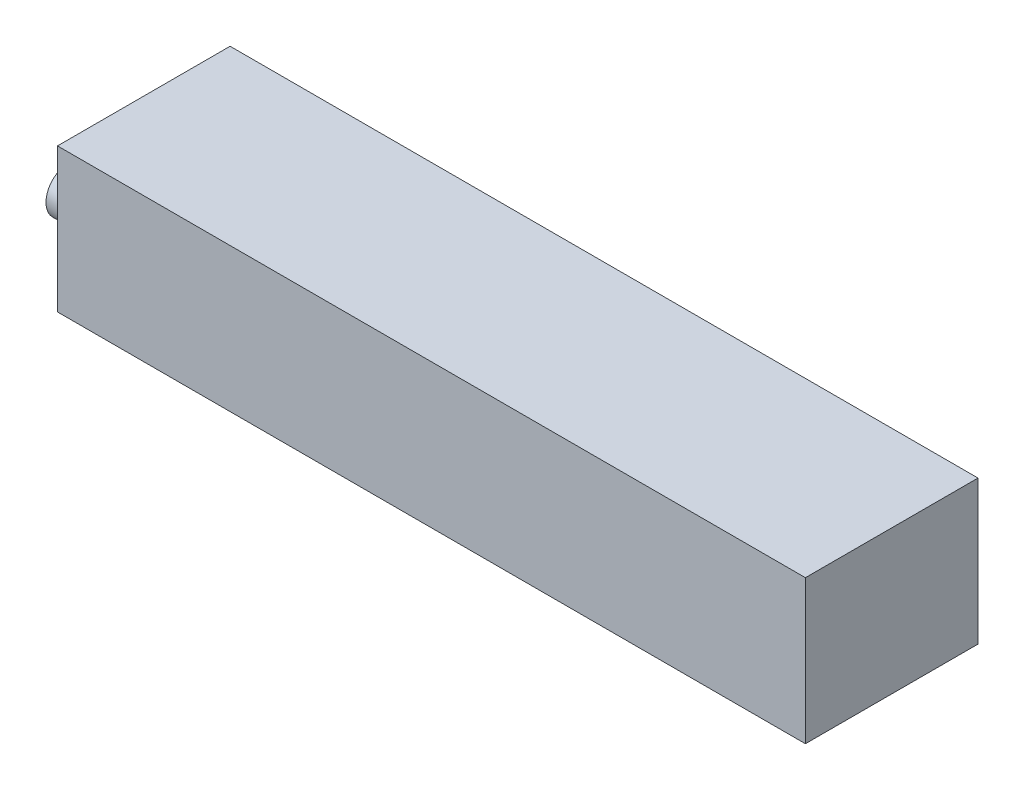
SolidWorks part; units mm, degrees
ref_plane "前视基准面" through (0, 0, 0) normal (0, 0, 1) x (1, 0, 0)
ref_plane "上视基准面" through (0, 0, 0) normal (0, 1, 0) x (1, 0, 0)
ref_plane "右视基准面" through (0, 0, 0) normal (1, 0, 0) x (0, 0, -1)
sketch "草图1" plane through (0, 0, 0) normal (0, 1, 0) x (1, 0, 0)
  line L1 (-65, 15) -> (65, 15)
  line L2 (-65, 15) -> (-65, -15)
  line L3 (-65, -15) -> (65, -15)
  line L4 (65, 15) -> (65, -15)
  line L5 (-65, 15) -> (65, -15) construction
  line L6 (-65, -15) -> (65, 15) construction
  point P0 (0, 0)
  dimension "D1" = 30
  dimension "D2" = 130
extrude "凸台-拉伸1" add sketch "草图1" along normal blind 25
sketch "草图2" plane through (-65, 0, 0) normal (-1, 0, 0) x (0, 0, 1)
  line L0 (-24.2902, 12.5) -> (21.2758, 12.5) construction
  line L1 (0, -5.4953) -> (0, 34.1866) construction
  circle A0 centre (-8, 12.5) radius 4
  circle A1 centre (8, 12.5) radius 4
  dimension "D1" = 8
  dimension "D3" = 8
  dimension "D2" = 8
extrude "凸台-拉伸2" add sketch "草图2" along normal blind 5
